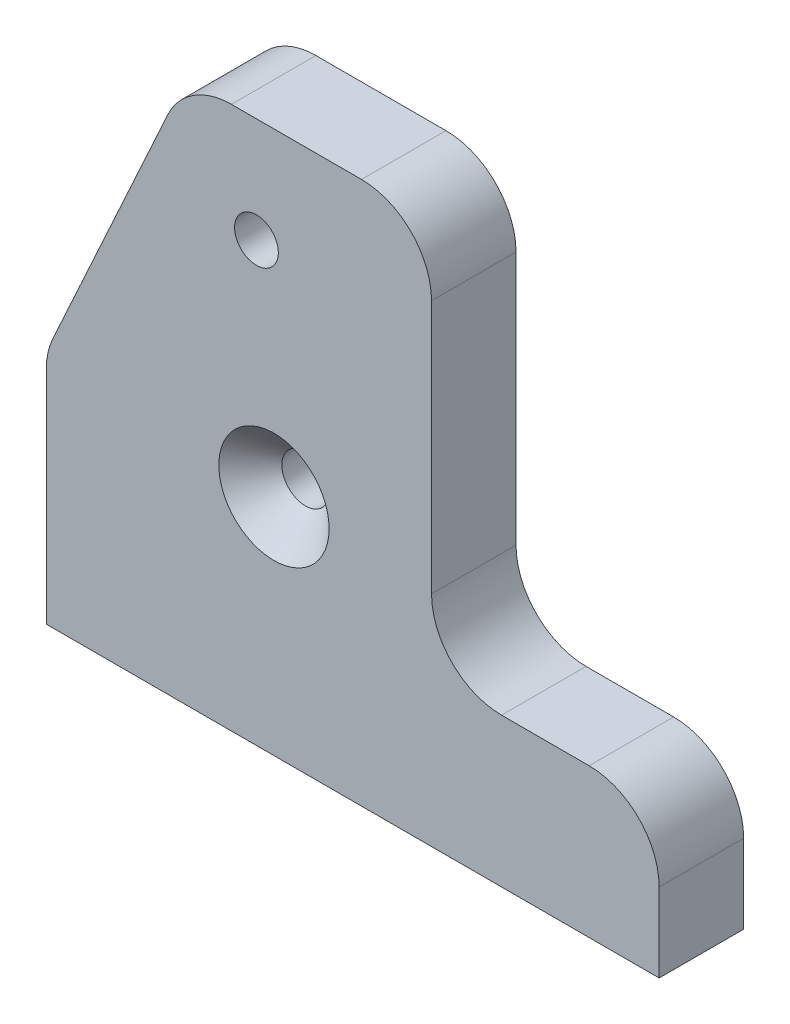
SolidWorks part; units mm, degrees
material "6061 Alloy"
ref_plane "Front" through (0, 0, 0) normal (0, 0, 1) x (1, 0, 0)
ref_plane "Top" through (0, 0, 0) normal (0, 1, 0) x (1, 0, 0)
ref_plane "Right" through (0, 0, 0) normal (1, 0, 0) x (0, 0, -1)
sketch "Sketch1" plane through (0, 0, 0) normal (0, 0, 1) x (1, 0, 0)
  line L0 (0, 0) -> (0, 13.5)
  line L9 (35, 0) -> (0, 0)
  line L15 (8, 31) -> (22, 31)
  line L16 (22, 31) -> (22, 8.5)
  line L17 (22, 8.5) -> (35, 8.5)
  line L18 (35, 8.5) -> (35, 0)
  line L22 (8, 31) -> (0, 13.5)
  dimension "D3" = 13.5
  dimension "D1" = 35
  dimension "D2" = 13
  dimension "D4" = 14
  dimension "D5" = 31
  dimension "D6" = 8.5
extrude "Boss-Extrude1" add sketch "Sketch1" along normal blind 4.826
hole_wizard "M3x0.5 Tapped Hole2" positions "Sketch13" profile "Sketch14" tap size "M3x0.5" standard "ANSI Metric" end condition through all
sketch "Sketch13" plane through (0, 0, 4.826) normal (0, 0, 1) x (1, 0, 0)
  line L2 (35, 0) -> (0, 0) construction
  point P5 (12, 25)
  dimension "D1" = 25
  dimension "D2" = 12
sketch "Sketch14" plane through (12, 25, 4.826) normal (1, 0, 0) x (0, -1, 0)
  line L0 (0, 0) -> (0, 4.826)
  line L1 (0, 4.826) -> (1.25, 4.826)
  line L2 (1.25, 4.826) -> (1.25, 0)
  line L5 (1.25, 0) -> (0, 0)
  line L11 (0, -6.35) -> (0, 107.95) construction
  dimension "Thru Tap Drill Dia." = 2.5
  dimension "Thru Tap Drill Depth" = 4.826
cosmetic thread "Hole Thread1" parameters "D2"=3
sketch "Sketch16" plane through (0, 0, 0) normal (0, -1, 0) x (1, 0, 0)
  line L0 (0, 4.826) -> (0, 0) construction
  line L3 (0, 2.413) -> (42.6944, 2.413) construction
  point P0 (28.73, 2.413)
  point P1 (16.73, 2.413)
  dimension "D1" = 16.73
  dimension "D2" = 12
hole_wizard "M3x0.5 Tapped Hole3" positions "Sketch17" profile "Sketch18" tap size "M3x0.5" standard "ANSI Metric"
sketch "Sketch17" plane through (0, 0, 0) normal (0, -1, 0) x (-1, 0, 0)
  point P0 (-16.73, -2.413)
  point P3 (-28.73, -2.413)
sketch "Sketch18" plane through (16.73, 0, 2.413) normal (1, 0, 0) x (0, 0, -1)
  line L0 (0, 0) -> (0, 5.7511)
  line L1 (0, 5.7511) -> (1.25, 5)
  line L2 (1.25, 5) -> (1.25, 0)
  line L5 (1.25, 0) -> (0, 0)
  line L10 (0, 5.7511) -> (-1.25, 5) construction
  line L11 (0, -6.35) -> (0, 107.95) construction
  dimension "Tap Drill Dia." = 2.5
  dimension "Tap Drill Depth" = 5
  dimension "Drill Angle" = 118
chamfer "Chamfer1" [suppressed] distance 13 distance2 10
fillet "Fillet2" radius 4 5 edges at (35, 8.5, 2.413) (22, 8.5, 2.413) (22, 31, 2.413) (0, 13.5, 2.413) (8, 31, 2.413)
sketch "Sketch19" plane through (0, 0, 4.826) normal (0, 0, 1) x (1, 0, 0)
  line L0 (12, 25) -> (12, 12.8)
  line L1 (12, 12.8) -> (13, 12.8)
  circle A0 centre (13, 12.8) radius 1.25
  dimension "D3" = 2.5
  dimension "D1" = 12.2
  dimension "D2" = 1
extrude "Cut-Extrude1" cut sketch "Sketch19" against normal blind 10
hole_wizard "CSK for M3 Flat Head Machine Screw1" positions "Sketch20" profile "Sketch22" countersink size "M3" standard "ANSI Metric" end condition through all
sketch "Sketch20" plane through (0, 0, 4.826) normal (0, 0, 1) x (1, 0, 0)
  point P0 (13, 12.8)
sketch "Sketch22" plane through (13, 12.8, 4.826) normal (1, 0, 0) x (0, -1, 0)
  line L0 (0, 0) -> (0, 4.826)
  line L1 (0, 4.826) -> (1.35, 4.826)
  line L2 (1.35, 4.826) -> (1.35, 1.8)
  line L3 (1.35, 1.8) -> (3.15, 0)
  line L5 (3.15, 0) -> (0, 0)
  line L6 (-1.35, 1.8) -> (-3.15, 0) construction
  line L11 (0, -6.35) -> (0, 107.95) construction
  dimension "Thru Hole Dia." = 2.7
  dimension "Thru Hole Depth" = 4.826
  dimension "Near C'Sink Dia." = 6.3
  dimension "Near C'Sink Angle" = 90
